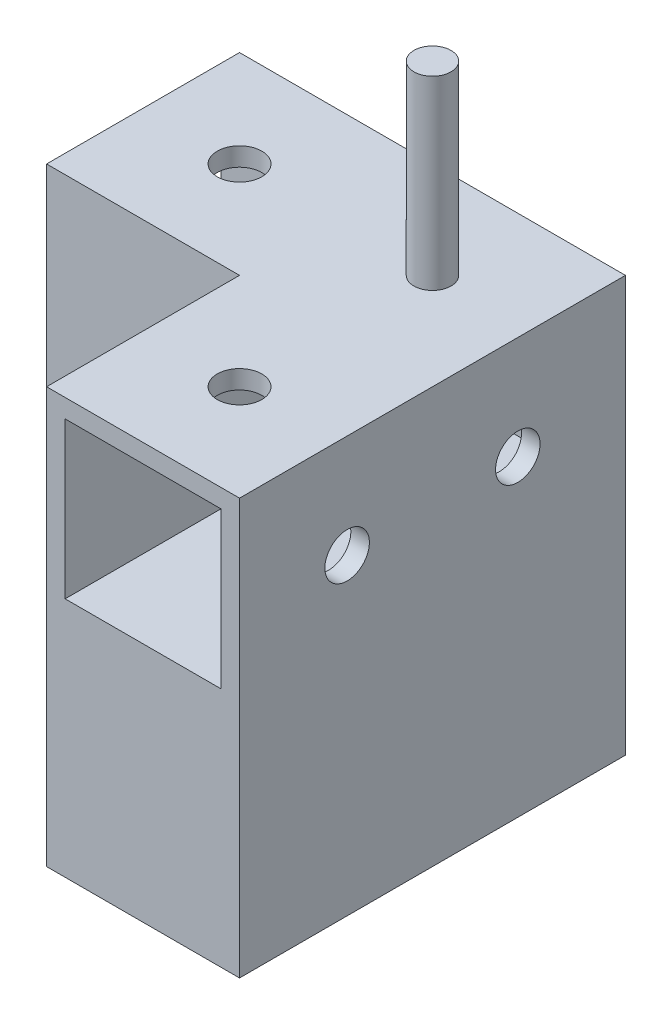
SolidWorks part; units mm, degrees
ref_plane "Front Plane" through (0, 0, 0) normal (0, 0, 1) x (1, 0, 0)
ref_plane "Top Plane" through (0, 0, 0) normal (0, 1, 0) x (1, 0, 0)
ref_plane "Right Plane" through (0, 0, 0) normal (1, 0, 0) x (0, 0, -1)
sketch "Sketch1" plane through (0, 0, 0) normal (0, 1, 0) x (1, 0, 0)
  line L1 (0, -26) -> (26, -26)
  line L2 (-26, 0) -> (-26, 26)
  line L3 (-26, 26) -> (26, 26)
  line L4 (26, -26) -> (26, 26)
  line L9 (-26, 0) -> (0, 0)
  line L10 (0, -26) -> (0, 0)
  point P0 (0, 0)
  dimension "D1" = 26
  dimension "D2" = 26
  dimension "D3" = 26
extrude "Boss-Extrude1" add sketch "Sketch1" along normal blind 3
sketch "Sketch2" plane through (0, 3, 0) normal (0, 1, 0) x (1, 0, 0)
  line L0 (0, 0) -> (26, 26) construction
  circle A0 centre (13, 13) radius 2.5
  dimension "D1" = 5
extrude "Boss-Extrude2" add sketch "Sketch2" along normal blind 25 contours A0
sketch "Sketch5" plane through (0, 3, 0) normal (0, 1, 0) x (1, 0, 0)
  line L0 (0, -13) -> (26, -13) construction
  line L1 (26, 26) -> (-26, 26) construction
  line L2 (0, 0) -> (0, -26) construction
  line L3 (-13, 26) -> (-13, 0) construction
  line L4 (-26, 0) -> (0, 0) construction
  line L5 (26, -26) -> (26, 26) construction
  line L6 (0, 0) -> (0, 26) construction
  line L7 (0, 0) -> (26, 0) construction
  line L8 (-26, 26) -> (-26, 0) construction
  line L9 (0, -26) -> (26, -26) construction
  circle A0 centre (-13, 13) radius 3
  circle A1 centre (13, -13) radius 3
  dimension "D1" = 13
  dimension "D3" = 6
  dimension "D2" = 13
extrude "Cut-Extrude1" cut sketch "Sketch5" against normal up to next
sketch "Sketch7" plane through (0, 0, 0) normal (0, -1, 0) x (1, 0, 0)
  line L0 (23, -23) -> (23, 23)
  line L1 (23, 23) -> (3, 23)
  line L2 (3, 23) -> (3, -3)
  line L3 (3, -3) -> (-23, -3)
  line L4 (-23, -3) -> (-23, -23)
  line L5 (-23, -23) -> (23, -23)
  line L6 (26, -26) -> (26, 26)
  line L7 (26, 26) -> (0, 26)
  line L8 (0, 26) -> (0, 0)
  line L9 (0, 0) -> (-26, 0)
  line L10 (-26, 0) -> (-26, -26)
  line L11 (-26, -26) -> (26, -26)
  line L12 (26, -26) -> (26, 26)
  line L13 (26, 26) -> (0, 26)
  line L14 (0, 26) -> (0, 0)
  line L15 (0, 0) -> (-26, 0)
  line L16 (-26, 0) -> (-26, -26)
  line L17 (-26, -26) -> (26, -26)
  dimension "D1" = 0
  dimension "D2" = 3
extrude "Boss-Extrude3" add sketch "Sketch7" along normal blind 20
sketch "Sketch8" plane through (0, -20, 0) normal (0, -1, 0) x (1, 0, 0)
  line L6 (-26, -26) -> (26, -26)
  line L7 (26, -26) -> (26, 26)
  line L8 (26, 26) -> (0, 26)
  line L9 (0, 26) -> (0, 0)
  line L10 (0, 0) -> (-26, 0)
  line L11 (-26, 0) -> (-26, -26)
  line L12 (-26, -26) -> (26, -26)
  line L13 (26, -26) -> (26, 26)
  line L14 (26, 26) -> (0, 26)
  line L15 (0, 26) -> (0, 0)
  line L16 (0, 0) -> (-26, 0)
  line L17 (-26, 0) -> (-26, -26)
  dimension "D1" = 0
extrude "Boss-Extrude4" add sketch "Sketch8" along normal blind 3
sketch "Sketch9" plane through (0, 0, 26) normal (0, 0, 1) x (1, 0, 0)
  line L0 (2.5, 0.5) -> (2.5, -20.5)
  line L1 (2.5, -20.5) -> (23.5, -20.5)
  line L2 (23.5, -20.5) -> (23.5, 0.5)
  line L3 (23.5, 0.5) -> (2.5, 0.5)
  line L4 (0, 3) -> (0, -23)
  line L5 (0, -23) -> (26, -23)
  line L6 (26, -23) -> (26, 3)
  line L7 (26, 3) -> (0, 3)
  line L8 (0, 3) -> (0, -23)
  line L9 (0, -23) -> (26, -23)
  line L10 (26, -23) -> (26, 3)
  line L11 (26, 3) -> (0, 3)
  dimension "D1" = 0
  dimension "D2" = 2.5
extrude "Cut-Extrude3" cut sketch "Sketch9" against normal offset from surface (49 mm away) 3 contours L2 L3 L0 L1 up to face at (0, -10, -26)
sketch "Sketch10" plane through (-26, 0, 0) normal (-1, 0, 0) x (0, 0, 1)
  line L0 (-23.5, 0.5) -> (-23.5, -20.5)
  line L1 (-23.5, -20.5) -> (-2.5, -20.5)
  line L2 (-2.5, -20.5) -> (-2.5, 0.5)
  line L3 (-2.5, 0.5) -> (-23.5, 0.5)
  line L4 (-26, 3) -> (-26, -23)
  line L5 (-26, -23) -> (0, -23)
  line L6 (0, -23) -> (0, 3)
  line L7 (0, 3) -> (-26, 3)
  line L8 (-26, 3) -> (-26, -23)
  line L9 (-26, -23) -> (0, -23)
  line L10 (0, -23) -> (0, 3)
  line L11 (0, 3) -> (-26, 3)
  dimension "D1" = 0
  dimension "D2" = 2.5
extrude "Cut-Extrude4" cut sketch "Sketch10" against normal offset from surface (49 mm away) 3 contours L2 L3 L0 L1 up to face at (26, -10, 0)
sketch "Sketch11" plane through (0, -23, 0) normal (0, -1, 0) x (1, 0, 0)
  line L6 (-26, 0) -> (-26, -26)
  line L7 (-26, -26) -> (26, -26)
  line L8 (26, -26) -> (26, 26)
  line L9 (26, 26) -> (0, 26)
  line L10 (0, 26) -> (0, 0)
  line L11 (0, 0) -> (-26, 0)
  line L12 (-26, 0) -> (-26, -26)
  line L13 (-26, -26) -> (26, -26)
  line L14 (26, -26) -> (26, 26)
  line L15 (26, 26) -> (0, 26)
  line L16 (0, 26) -> (0, 0)
  line L17 (0, 0) -> (-26, 0)
  dimension "D1" = 0
extrude "Boss-Extrude5" add sketch "Sketch11" along normal blind 30
sketch "Sketch12" plane through (0, 0, -26) normal (0, 0, -1) x (-1, 0, 0)
  line L0 (0, 3) -> (0, -20) construction
  line L1 (26, -20) -> (0, -20) construction
  line L2 (0, -20) -> (-26, -20) construction
  line L6 (-26, 3) -> (-26, -53) construction
  line L7 (-26, 3) -> (26, 3) construction
  line L9 (-26, 0) -> (0, 0) construction
  line L11 (-13, 0) -> (-13, -20) construction
  line L12 (13, 0) -> (13, -20) construction
  line L13 (0, 0) -> (26, 0) construction
  line L14 (26, 3) -> (26, -53) construction
  circle A0 centre (-13, -10) radius 3
  circle A1 centre (13, -10) radius 3
  point P5 (0, 0)
  dimension "D4" = 6
  dimension "D1" = 20
extrude "Cut-Extrude5" cut sketch "Sketch12" against normal up to next
sketch "Sketch13" plane through (26, 0, 0) normal (1, 0, 0) x (0, 0, -1)
  line L0 (0, 3) -> (0, -53) construction
  line L1 (-26, 3) -> (26, 3) construction
  line L2 (26, -53) -> (-26, -53) construction
  line L3 (-11.5, -10.9175) -> (11.5, -10.9175) construction
  circle A0 centre (-11.5, -10.9175) radius 3
  circle A1 centre (11.5, -10.9175) radius 3
  dimension "D2" = 6
  dimension "D1" = 11.5
extrude "Cut-Extrude6" cut sketch "Sketch13" against normal up to next
sketch "Sketch14" plane through (0, -53, 0) normal (0, -1, 0) x (1, 0, 0)
  line L0 (5, -5) -> (-21, -5)
  line L1 (-21, -5) -> (-21, -21)
  line L2 (-21, -21) -> (21, -21)
  line L3 (21, -21) -> (21, 21)
  line L4 (21, 21) -> (5, 21)
  line L5 (5, 21) -> (5, -5)
  line L6 (0, 0) -> (-26, 0)
  line L7 (-26, 0) -> (-26, -26)
  line L8 (-26, -26) -> (26, -26)
  line L9 (26, -26) -> (26, 26)
  line L10 (26, 26) -> (0, 26)
  line L11 (0, 26) -> (0, 0)
  line L12 (0, 0) -> (-26, 0)
  line L13 (-26, 0) -> (-26, -26)
  line L14 (-26, -26) -> (26, -26)
  line L15 (26, -26) -> (26, 26)
  line L16 (26, 26) -> (0, 26)
  line L17 (0, 26) -> (0, 0)
  dimension "D1" = 0
  dimension "D2" = 5
extrude "Cut-Extrude8" cut sketch "Sketch14" against normal blind 29 flip side to cut
